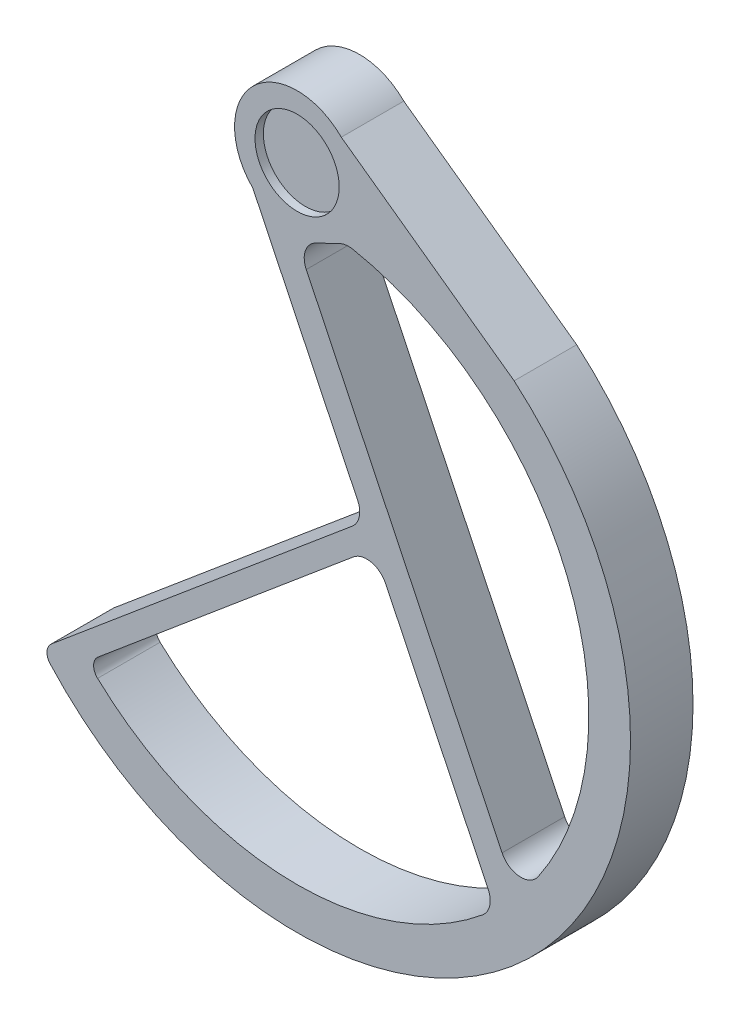
SolidWorks part; units mm, degrees
ref_plane "正面" through (0, 0, 0) normal (0, 0, 1) x (1, 0, 0)
ref_plane "平面" through (0, 0, 0) normal (0, 1, 0) x (1, 0, 0)
ref_plane "右側面" through (0, 0, 0) normal (1, 0, 0) x (0, 0, -1)
sketch "ｽｹｯﾁ4" plane through (0, 0, 0) normal (0, 0, 1) x (1, 0, 0)
  line L0 (0, 0.7897) -> (0, 0)
  line L1 (-53.6231, -124.9951) -> (-58.9406, -129.4571)
  line L3 (-10.6066, -10.6066) -> (14.5363, -62.8896)
  line L4 (-53.6231, -124.9951) -> (13.2442, -68.8868)
  line L5 (21.2324, -76.8138) -> (45.8448, -127.9938)
  line L6 (10.6066, 10.6066) -> (52.0762, -19.2705)
  line L7 (-58.0696, -135.2532) -> (-57.9498, -135.1527)
  line L8 (-47.7477, -126.5866) -> (13.5112, -75.1515)
  arc A1 (-59.2335, -133.7716) -> (52.0762, -19.2705) centre (0, -80) ccw
  arc A2 (-47.8702, -131.073) -> (44.5187, -134.0193) centre (0, -80) ccw
  arc A3 (10.6066, 10.6066) -> (-10.6066, -10.6066) centre (0, 0) ccw
  arc A4 (-59.2335, -133.7716) -> (-58.9406, -129.4571) centre (-57.0123, -131.7552) cw
  arc A5 (-47.8702, -131.073) -> (-47.7477, -126.5866) centre (-45.8186, -128.8841) cw
  arc A6 (13.5112, -75.1515) -> (21.2324, -76.8138) centre (16.7264, -78.9807) cw
  arc A7 (13.2442, -68.8868) -> (14.5363, -62.8896) centre (10.0302, -65.0566) ccw
  arc A8 (45.8448, -127.9938) -> (44.5187, -134.0193) centre (41.3388, -130.1608) cw
  point P18 (-61.2836, -131.423)
  point P21 (-50.2744, -128.7081)
  point P24 (18.4421, -71.0114)
  dimension "D3" = 140
  dimension "D4" = 30
  dimension "D5" = 5
  dimension "D6" = 3
  dimension "D7" = 3
  dimension "D8" = 5
  dimension "D9" = 5
  dimension "D10" = 5
  dimension "D2" = 5
extrude "ﾎﾞｽ - 押し出し1" add sketch "ｽｹｯﾁ4" along normal blind 15
sketch "ｽｹｯﾁ6" plane through (0, 0, 15) normal (0, 0, 1) x (1, 0, 0)
  line L6 (49.1896, -118.7973) -> (2.2018, -21.089)
  line L7 (6.4834, -13.4819) -> (4.5408, -14.416)
  line L8 (6.4834, -13.4819) -> (10.2197, -11.6851)
  arc A0 (57.8261, -119.448) -> (13.3394, -11.2828) centre (0, -80) ccw
  arc A1 (2.2018, -21.089) -> (4.5408, -14.416) centre (6.7078, -18.9221) cw
  arc A2 (13.3394, -11.2828) -> (10.2197, -11.6851) centre (12.3866, -16.1911) ccw
  arc A3 (57.8261, -119.448) -> (49.1896, -118.7973) centre (53.6956, -116.6303) cw
  point P7 (0.0348, -16.583)
  point P14 (52.6925, -126.0814)
  dimension "D3" = 121.502
  dimension "D4" = 70
  dimension "D1" = 5
  dimension "D2" = 5
  dimension "D5" = 5
  dimension "D6" = 90
extrude "ｶｯﾄ - 押し出し1" cut sketch "ｽｹｯﾁ6" against normal blind 15
sketch "ｽｹｯﾁ7" plane through (0, 0, 15) normal (0, 0, 1) x (1, 0, 0)
  circle A0 centre (0, 0) radius 10.1
extrude "ｶｯﾄ - 押し出し2" cut sketch "ｽｹｯﾁ7" against normal blind 2
